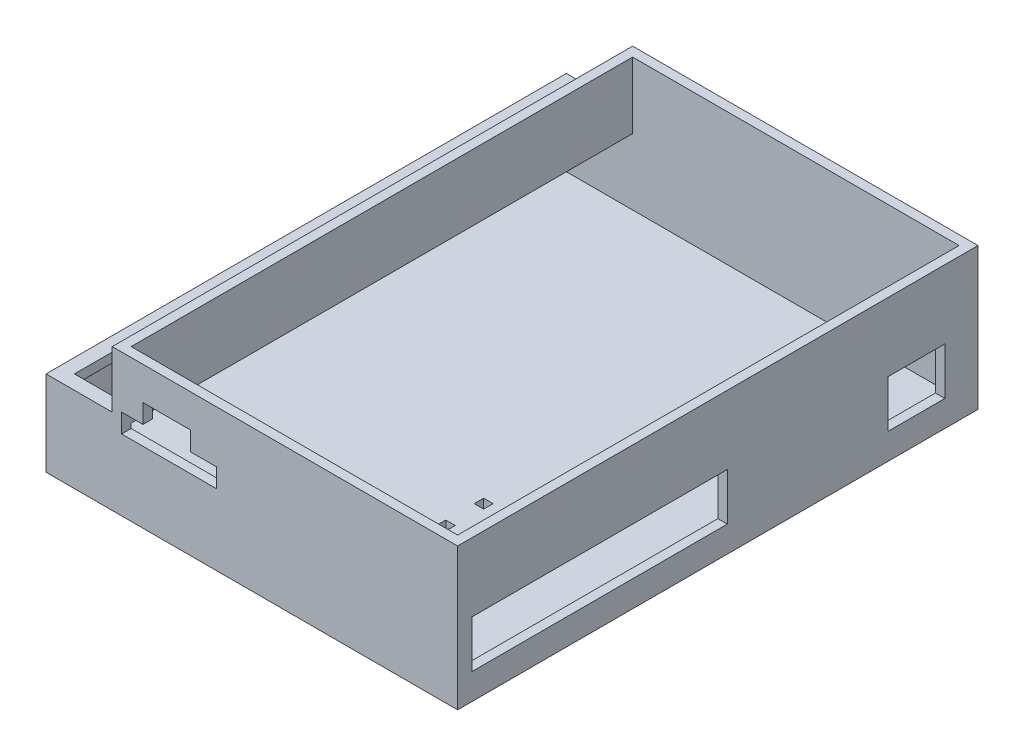
SolidWorks part; units mm, degrees
ref_plane "Ön Düzlem" through (0, 0, 0) normal (0, 0, 1) x (1, 0, 0)
ref_plane "Üst Düzlem" through (0, 0, 0) normal (0, 1, 0) x (1, 0, 0)
ref_plane "Sağ Düzlem" through (0, 0, 0) normal (1, 0, 0) x (0, 0, -1)
sketch "Çizim2" plane through (0, 0, 0) normal (0, 1, 0) x (1, 0, 0)
  line L1 (0, 0) -> (87, 0)
  line L2 (0, 0) -> (0, 110)
  line L3 (0, 110) -> (87, 110)
  line L4 (87, 0) -> (87, 110)
  dimension "D1" = 110
  dimension "D2" = 87
extrude "Yükseklik-Ekstrüzyon1" add sketch "Çizim2" along normal blind 28
shell "İç Boşaltma1" thickness 2
sketch "Çizim3" plane through (0, 0, 0) normal (-1, 0, 0) x (0, 0, 1)
  line L0 (-110, 28) -> (-110, 0) construction
  line L1 (-106, 13.5) -> (-40, 13.5)
  line L2 (-106, 13.5) -> (-106, 3.5)
  line L3 (-106, 3.5) -> (-40, 3.5)
  line L4 (-40, 13.5) -> (-40, 3.5)
  line L5 (-110, 0) -> (0, 0) construction
  dimension "D1" = 4
  dimension "D2" = 3.5
  dimension "D3" = 10
  dimension "D4" = 66
extrude "Kes-Ekstrüzyon1" cut sketch "Çizim3" against normal blind 2
sketch "Çizim4" plane through (0, 0, -110) normal (0, 0, -1) x (-1, 0, 0)
  line L1 (0, 28) -> (-14, 28)
  line L2 (0, 28) -> (0, 14)
  line L3 (0, 14) -> (-14, 14)
  line L4 (-14, 28) -> (-14, 14)
  dimension "D1" = 14
  dimension "D2" = 14
extrude "Kes-Ekstrüzyon3" cut sketch "Çizim4" against normal blind 110
sketch "Çizim5" plane through (0, 14, 0) normal (0, 1, 0) x (1, 0, 0)
  line L1 (0, 110) -> (16, 110)
  line L2 (0, 110) -> (0, 0)
  line L3 (0, 0) -> (16, 0)
  line L4 (16, 110) -> (16, 0)
  line L6 (14, 0) -> (87, 0) construction
  line L7 (87, 110) -> (14, 110) construction
  line L8 (14, 108) -> (14, 110) construction
  point P6 (14, 110)
  point P7 (14, 110)
  point P8 (16.0232, 0)
  point P9 (0, 0)
  point P12 (16.0001, 110)
  dimension "D1" = 2
extrude "Yükseklik-Ekstrüzyon2" add sketch "Çizim5" along normal blind 2
sketch "Çizim7" plane through (0, 16, 0) normal (0, 1, 0) x (1, 0, 0)
  line L0 (0, 0) -> (14, 0) construction
  line L1 (13, 3) -> (3, 3)
  line L2 (13, 3) -> (13, 37)
  line L3 (13, 37) -> (3, 37)
  line L4 (3, 3) -> (3, 37)
  line L5 (0, 110) -> (0, 0) construction
  dimension "D1" = 3
  dimension "D2" = 3
  dimension "D3" = 34
  dimension "D4" = 10
extrude "Kes-Ekstrüzyon4" cut sketch "Çizim7" against normal blind 1
sketch "Çizim8" plane through (0, 0, 0) normal (0, 0, 1) x (1, 0, 0)
  line L0 (0, 0) -> (87, 0) construction
  line L1 (16, 17) -> (36, 17)
  line L2 (16, 17) -> (16, 13)
  line L3 (16, 13) -> (36, 13)
  line L4 (36, 17) -> (36, 13)
  line L5 (0, 16) -> (0, 0) construction
  line L6 (20.5, 17) -> (30.5, 17)
  line L7 (20.5, 17) -> (20.5, 21)
  line L8 (20.5, 21) -> (30.5, 21)
  line L9 (30.5, 17) -> (30.5, 21)
  point P10 (16, 15)
  dimension "D1" = 13
  dimension "D2" = 4
  dimension "D3" = 4
  dimension "D4" = 4.5
  dimension "D5" = 20
  dimension "D6" = 10
  dimension "D7" = 16
extrude "Kes-Ekstrüzyon5" cut sketch "Çizim8" against normal blind 2 contours L1 L9 L8 L7 | L4 L1 L2 L3
sketch "Çizim9" plane through (87, 0, 0) normal (1, 0, 0) x (0, 0, -1)
  line L0 (0, 28) -> (0, 0) construction
  line L1 (3, 13.5) -> (57, 13.5)
  line L2 (3, 13.5) -> (3, 3.5)
  line L3 (3, 3.5) -> (57, 3.5)
  line L4 (57, 13.5) -> (57, 3.5)
  line L5 (0, 0) -> (110, 0) construction
  dimension "D1" = 3
  dimension "D2" = 57
  dimension "D3" = 3.5
  dimension "D4" = 10
extrude "Kes-Ekstrüzyon6" cut sketch "Çizim9" against normal blind 2
sketch "Çizim10" plane through (0, 0, 0) normal (0, -1, 0) x (1, 0, 0)
  line L1 (0, 0) -> (87, 0)
  line L2 (0, 0) -> (0, -110)
  line L3 (0, -110) -> (87, -110)
  line L4 (87, 0) -> (87, -110)
extrude "Yükseklik-Ekstrüzyon4" add sketch "Çizim10" along normal blind 2
sketch "Çizim11" plane through (87, 0, 0) normal (1, 0, 0) x (0, 0, -1)
  line L0 (110, 28) -> (110, -2) construction
  line L1 (91, 13.5) -> (103, 13.5)
  line L2 (91, 13.5) -> (91, 3.5)
  line L3 (91, 3.5) -> (103, 3.5)
  line L4 (103, 13.5) -> (103, 3.5)
  line L5 (110, -2) -> (0, -2) construction
  dimension "D1" = 7
  dimension "D2" = 19
  dimension "D3" = 10
  dimension "D4" = 5.5
extrude "Kes-Ekstrüzyon7" cut sketch "Çizim11" against normal blind 2
sketch "Çizim12" plane through (0, -2, 0) normal (0, -1, 0) x (1, 0, 0)
  line L0 (87, -110) -> (87, 0) construction
  line L1 (55, -5.5) -> (53, -5.5)
  line L2 (55, -5.5) -> (55, -7.5)
  line L3 (55, -7.5) -> (53, -7.5)
  line L4 (53, -5.5) -> (53, -7.5)
  line L5 (55, -37.5) -> (53, -37.5)
  line L6 (87, 0) -> (0, 0) construction
  line L7 (55, -21.5) -> (53, -21.5)
  line L8 (55, -13.5) -> (53, -13.5)
  line L9 (55, -13.5) -> (55, -15.5)
  line L10 (55, -15.5) -> (53, -15.5)
  line L11 (53, -13.5) -> (53, -15.5)
  line L12 (55, -21.5) -> (55, -23.5)
  line L13 (55, -23.5) -> (53, -23.5)
  line L14 (53, -21.5) -> (53, -23.5)
  line L15 (55, -29.5) -> (53, -29.5)
  line L16 (55, -29.5) -> (55, -31.5)
  line L17 (55, -31.5) -> (53, -31.5)
  line L18 (53, -29.5) -> (53, -31.5)
  line L19 (55, -37.5) -> (55, -39.5)
  line L20 (55, -39.5) -> (53, -39.5)
  line L21 (53, -37.5) -> (53, -39.5)
  dimension "D1" = 32
  dimension "D2" = 5.5
  dimension "D3" = 2
  dimension "D4" = 2
  dimension "D5" = 2
  dimension "D6" = 2
  dimension "D7" = 0
  dimension "D8" = 6
  dimension "D9" = 6
  dimension "D10" = 2
  dimension "D11" = 2
  dimension "D12" = 6
  dimension "D13" = 2
  dimension "D14" = 2
  dimension "D15" = 6
  dimension "D16" = 2
  dimension "D17" = 2
extrude "Kes-Ekstrüzyon8" cut sketch "Çizim12" against normal blind 2
sketch "Çizim14" plane through (0, 15, 0) normal (0, 1, 0) x (1, 0, 0)
  line L1 (3, 37) -> (13, 37)
  line L2 (3, 37) -> (3, 3)
  line L3 (3, 3) -> (13, 3)
  line L4 (13, 37) -> (13, 3)
extrude "Kes-Ekstrüzyon9" cut sketch "Çizim14" against normal blind 2
sketch "Çizim15" plane through (14, 0, 0) normal (-1, 0, 0) x (0, 0, 1)
  line L1 (-108, 28) -> (-2, 28)
  line L2 (-108, 28) -> (-108, 16)
  line L3 (-108, 16) -> (-2, 16)
  line L4 (-2, 28) -> (-2, 16)
  point P4 (-108, 28)
extrude "Yükseklik-Ekstrüzyon15" add sketch "Çizim15" against normal blind 2
